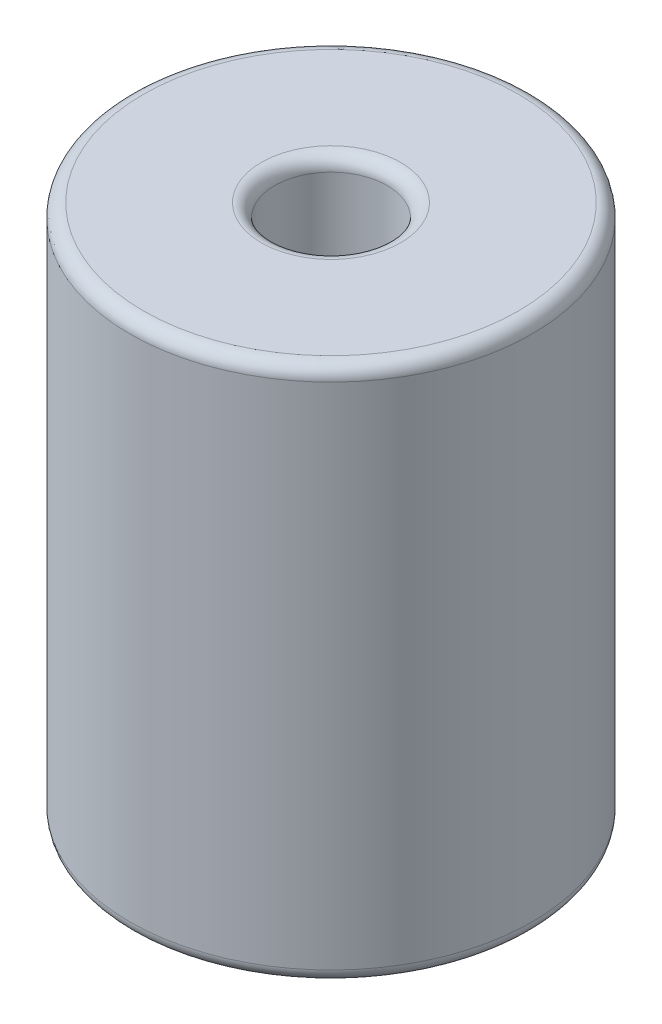
SolidWorks part; units mm, degrees
ref_plane "Front Plane" through (0, 0, 0) normal (0, 0, 1) x (1, 0, 0)
ref_plane "Top Plane" through (0, 0, 0) normal (0, 1, 0) x (1, 0, 0)
ref_plane "Right Plane" through (0, 0, 0) normal (1, 0, 0) x (0, 0, -1)
sketch "Sketch1" plane through (0, 0, 0) normal (0, 1, 0) x (1, 0, 0)
  circle A0 centre (0, 0) radius 7.5
  circle A1 centre (0, 0) radius 2.1
  dimension "D1" = 15
  dimension "D2" = 4.2
extrude "Boss-Extrude1" add sketch "Sketch1" along normal blind 20
fillet "Fillet1" radius 0.5 4 edges at (0, 0, 2.1) (0, 20, 2.1) (0, 0, 7.5) (0, 20, 7.5)
